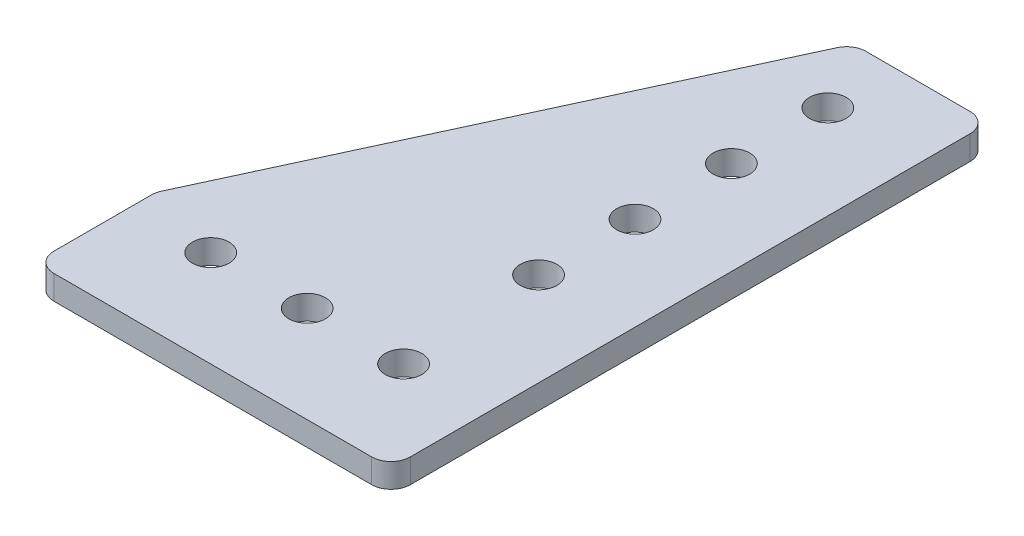
SolidWorks part; units mm, degrees
ref_plane "Front Plane" through (0, 0, 0) normal (0, 0, 1) x (1, 0, 0)
ref_plane "Top Plane" through (0, 0, 0) normal (0, 1, 0) x (1, 0, 0)
ref_plane "Right Plane" through (0, 0, 0) normal (1, 0, 0) x (0, 0, -1)
sketch "Sketch1" plane through (0, 0, 0) normal (0, 1, 0) x (1, 0, 0)
  line L1 (0, 0) -> (50.8, 0)
  line L2 (0, 0) -> (0, 82.55)
  line L3 (0, 82.55) -> (50.8, 82.55)
  line L4 (50.8, 0) -> (50.8, 82.55)
  dimension "D1" = 50.8
  dimension "D2" = 82.55
extrude "Boss-Extrude1" add sketch "Sketch1" along normal blind 3.175
sketch "Sketch2" plane through (0, 3.175, 0) normal (0, 1, 0) x (1, 0, 0)
  line L5 (50.8, 0) -> (50.8, 82.55) construction
  line L6 (0, 0) -> (50.8, 0) construction
  circle A0 centre (39.7527, 12.7) radius 2.413
  circle A5 centre (27.0527, 12.7) radius 2.413
  circle A6 centre (14.3527, 12.7) radius 2.413
  circle A7 centre (38.4827, 31.75) radius 2.413
  circle A9 centre (38.4827, 44.45) radius 2.413
  circle A10 centre (38.4827, 57.15) radius 2.413
  circle A11 centre (38.4827, 69.85) radius 2.413
  dimension "D1" = 4.826
  dimension "D2" = 3
  dimension "D3" = 4.826
  dimension "D5" = 12.3173
  dimension "D6" = 31.75
  dimension "D7" = 11.0473
  dimension "D8" = 12.7
  dimension "D4" = 4
extrude "Cut-Extrude1" cut sketch "Sketch2" against normal through all
sketch "Sketch3" plane through (0, 3.175, 0) normal (0, 1, 0) x (1, 0, 0)
  line L0 (3.8598, 0) -> (3.8598, 15.9468)
  line L1 (0, 0) -> (50.8, 0) construction
  line L2 (3.8598, 15.9468) -> (32.9069, 78.8086)
  line L3 (32.9069, 78.8086) -> (50.8, 78.8086)
  line L4 (50.8, 0) -> (50.8, 82.55) construction
  line L5 (50.8, 78.8086) -> (50.8, 82.55)
  line L6 (50.8, 82.55) -> (0, 82.55)
  line L7 (0, 82.55) -> (0, 0)
  line L8 (0, 0) -> (3.8598, 0)
extrude "Cut-Extrude2" cut sketch "Sketch3" against normal through all
fillet "Fillet1" radius 2.54 5 edges at (3.8598, 1.5875, -15.9468) (3.8598, 1.5875, 0) (50.8, 1.5875, 0) (50.8, 1.5875, -78.8086) (32.9069, 1.5875, -78.8086)
